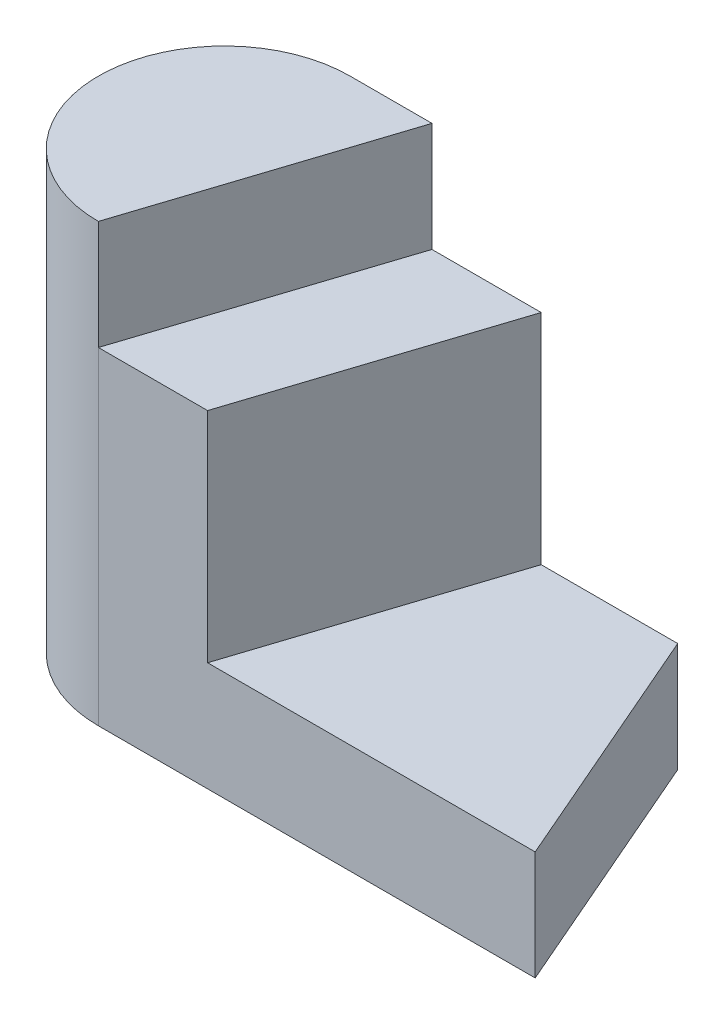
SolidWorks part; units mm, degrees
ref_plane "Front Plane" through (0, 0, 0) normal (0, 0, 1) x (1, 0, 0)
ref_plane "Top Plane" through (0, 0, 0) normal (0, 1, 0) x (1, 0, 0)
ref_plane "Right Plane" through (0, 0, 0) normal (1, 0, 0) x (0, 0, -1)
sketch "Sketch1" plane through (0, 0, 0) normal (0, 1, 0) x (1, 0, 0)
  line L0 (0, 11.5256) -> (30, 11.5256)
  line L1 (0, -11.5256) -> (40, -11.5256)
  line L2 (30, 11.5256) -> (40, -11.5256)
  arc A0 (0, 11.5256) -> (0, -11.5256) centre (0, 0) ccw
  dimension "D1" = 30
  dimension "D2" = 40
extrude "Boss-Extrude1" add sketch "Sketch1" along normal blind 10
sketch "Sketch2" plane through (0, 10, 0) normal (0, 1, 0) x (1, 0, 0)
  line L0 (7.4985, 11.5256) -> (17.4985, 11.5256)
  line L2 (30, 11.5256) -> (0, 11.5256) construction
  line L3 (7.4985, 11.5256) -> (0, -11.5256)
  line L4 (17.4985, 11.5256) -> (10, -11.5256)
  line L5 (0, -11.5256) -> (40, -11.5256) construction
  line L6 (0, -11.5256) -> (10, -11.5256)
  point P6 (12.4985, 11.5256)
  dimension "D1" = 10
extrude "Boss-Extrude2" add sketch "Sketch2" along normal blind 20 contours L3 L6 L4 L0
sketch "Sketch3" plane through (0, 10, 0) normal (0, 1, 0) x (1, 0, 0)
  line L0 (0, 11.5256) -> (7.4985, 11.5256)
  line L1 (7.4985, 11.5256) -> (0, -11.5256)
  arc A1 (0, 11.5256) -> (0, -11.5256) centre (0, 0) ccw
extrude "Boss-Extrude3" add sketch "Sketch3" along normal blind 30 contours A1 L1 L0
